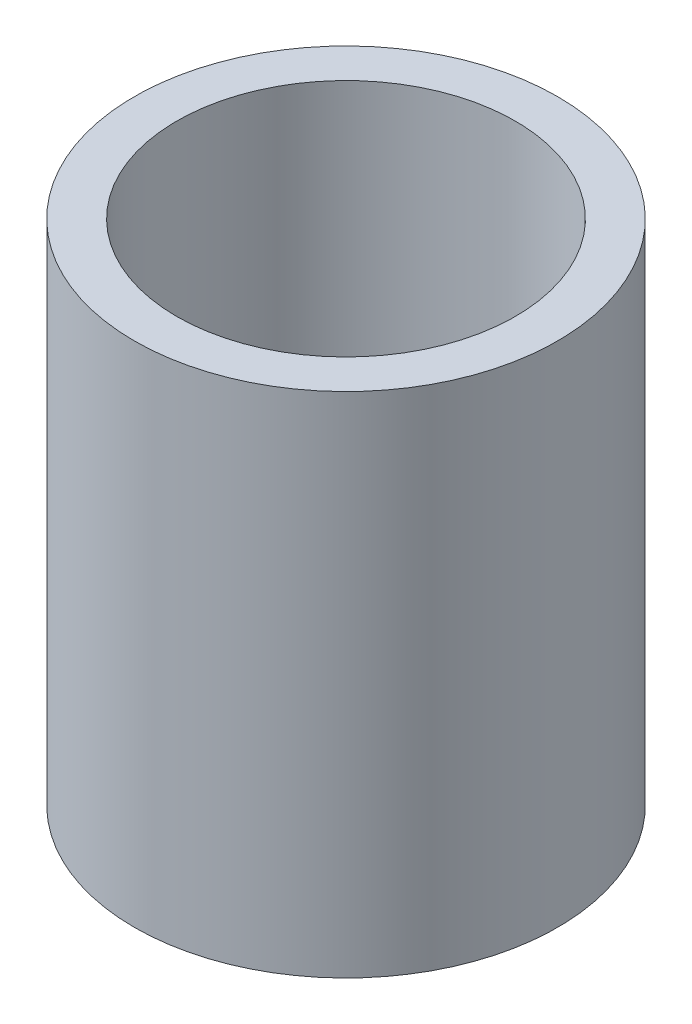
SolidWorks part; units mm, degrees
ref_plane "Plan de face" through (0, 0, 0) normal (0, 0, 1) x (1, 0, 0)
ref_plane "Plan de dessus" through (0, 0, 0) normal (0, 1, 0) x (1, 0, 0)
ref_plane "Plan de droite" through (0, 0, 0) normal (1, 0, 0) x (0, 0, -1)
sketch "Esquisse1" plane through (0, 0, 0) normal (0, 1, 0) x (1, 0, 0)
  circle A0 centre (0, 0) radius 25
  dimension "D1" = 50
extrude "Boss.-Extru.1" add sketch "Esquisse1" along normal blind 60
sketch "Esquisse2" plane through (0, 60, 0) normal (0, 1, 0) x (1, 0, 0)
  circle A0 centre (0, 0) radius 20
  dimension "D1" = 40
extrude "Enlèv. mat.-Extru.1" cut sketch "Esquisse2" against normal blind 55
